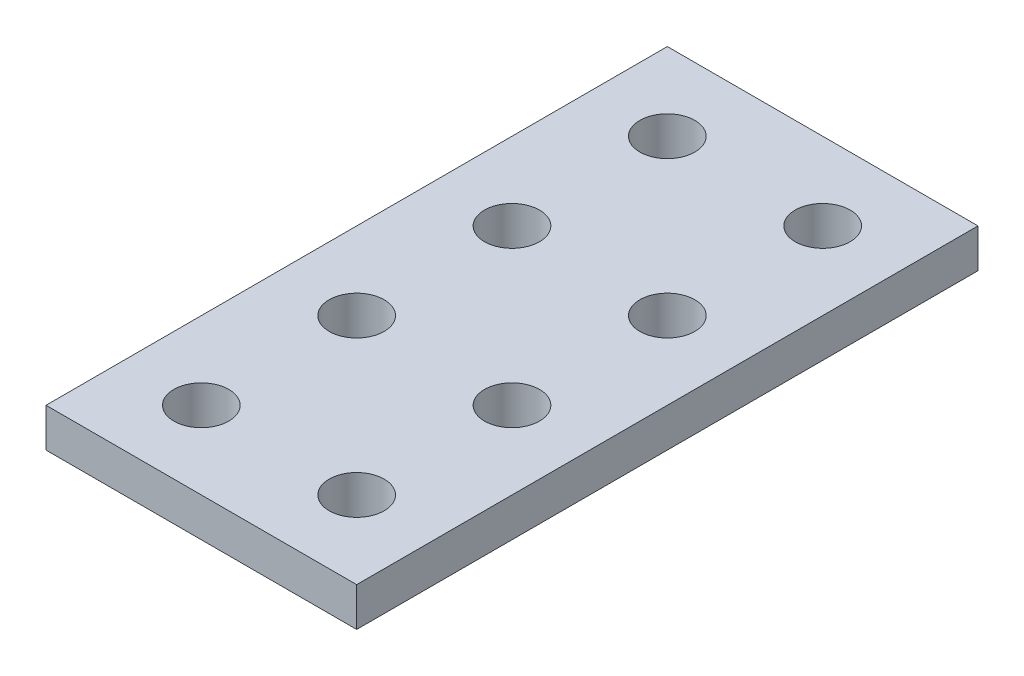
SolidWorks part; units mm, degrees
ref_plane "Front Plane" through (0, 0, 0) normal (0, 0, 1) x (1, 0, 0)
ref_plane "Top Plane" through (0, 0, 0) normal (0, 1, 0) x (1, 0, 0)
ref_plane "Right Plane" through (0, 0, 0) normal (1, 0, 0) x (0, 0, -1)
sketch "Sketch1" plane through (0, 0, 0) normal (0, 1, 0) x (1, 0, 0)
  line L1 (0, 0) -> (25.4, 0)
  line L2 (0, 0) -> (0, -50.8)
  line L3 (0, -50.8) -> (25.4, -50.8)
  line L4 (25.4, 0) -> (25.4, -50.8)
  circle A0 centre (6.35, -6.35) radius 2.2479
  circle A2 centre (19.05, -6.35) radius 2.2479
  circle A3 centre (19.05, -19.05) radius 2.2479
  circle A4 centre (19.05, -31.75) radius 2.2479
  circle A5 centre (19.05, -44.45) radius 2.2479
  circle A6 centre (6.35, -19.05) radius 2.2479
  circle A7 centre (6.35, -31.75) radius 2.2479
  circle A8 centre (6.35, -44.45) radius 2.2479
  point P8 (12.7, 0)
  point P9 (0, -25.4)
  point P28 (12.7, -25.4)
  dimension "D1" = 4.4958
  dimension "D4" = 12.7
  dimension "D5" = 12.7
  dimension "D6" = 25.4
  dimension "D7" = 50.8
  dimension "D9" = 38.1
  dimension "D10" = 6.35
  dimension "D8" = 6.35
  dimension "D2" = 2
  dimension "D3" = 4
extrude "Boss-Extrude1" add sketch "Sketch1" along normal blind 3.175
equation "\"D10@Sketch1\"=(\"D7@Sketch1\"-\"D9@Sketch1\")/2"
equation "\"D8@Sketch1\"=(\"D6@Sketch1\"-\"D4@Sketch1\")/2"
